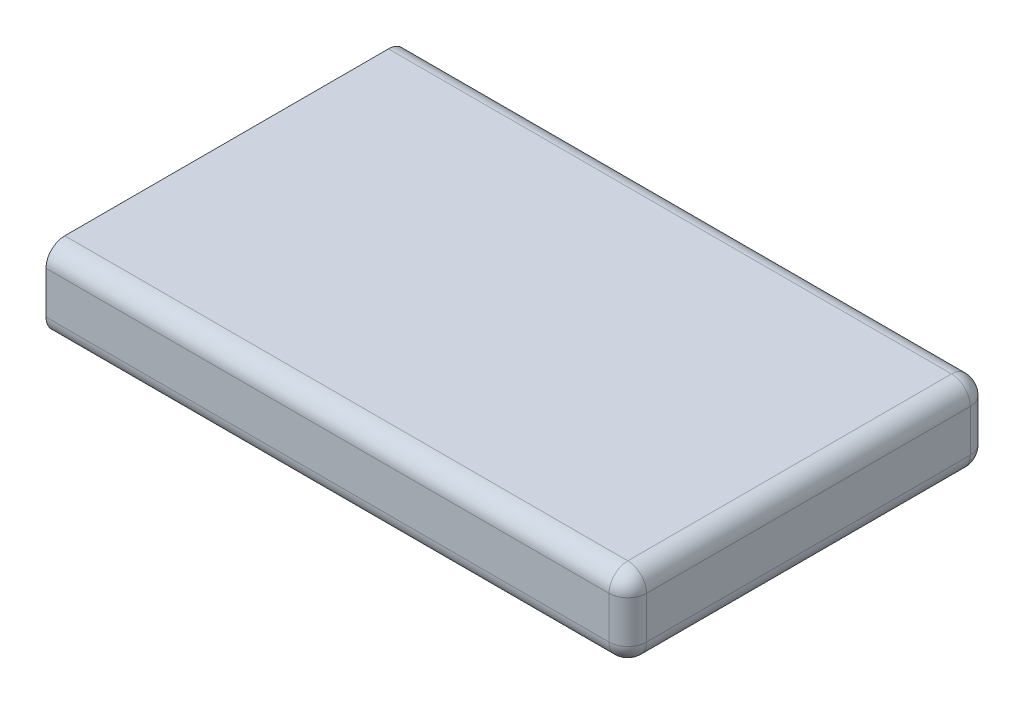
SolidWorks part; units mm, degrees
ref_plane "Front Plane" through (0, 0, 0) normal (0, 0, 1) x (1, 0, 0)
ref_plane "Top Plane" through (0, 0, 0) normal (0, 1, 0) x (1, 0, 0)
ref_plane "Right Plane" through (0, 0, 0) normal (1, 0, 0) x (0, 0, -1)
sketch "Sketch1" plane through (0, 0, 0) normal (0, 1, 0) x (1, 0, 0)
  line L1 (0, 0) -> (62, 0)
  line L2 (0, 0) -> (0, -38.5)
  line L3 (0, -38.5) -> (62, -38.5)
  line L4 (62, 0) -> (62, -38.5)
  dimension "D1" = 62
  dimension "D2" = 38.5
extrude "Boss-Extrude1" add sketch "Sketch1" along normal blind 8.5
fillet "Fillet1" radius 2 8 edges at (31, 0, 0) (31, 8.5, 0) (62, 4.25, 0) (62, 4.25, 38.5) (62, 0, 19.25) (62, 8.5, 19.25) (31, 0, 38.5) (31, 8.5, 38.5)
ref_plane "Plane1" through (0, 0, 19.25) normal (0, 0, 1) x (1, 0, 0)
ref_plane "Plane2" through (0, 4.25, 0) normal (0, -1, 0) x (-1, 0, 0)
